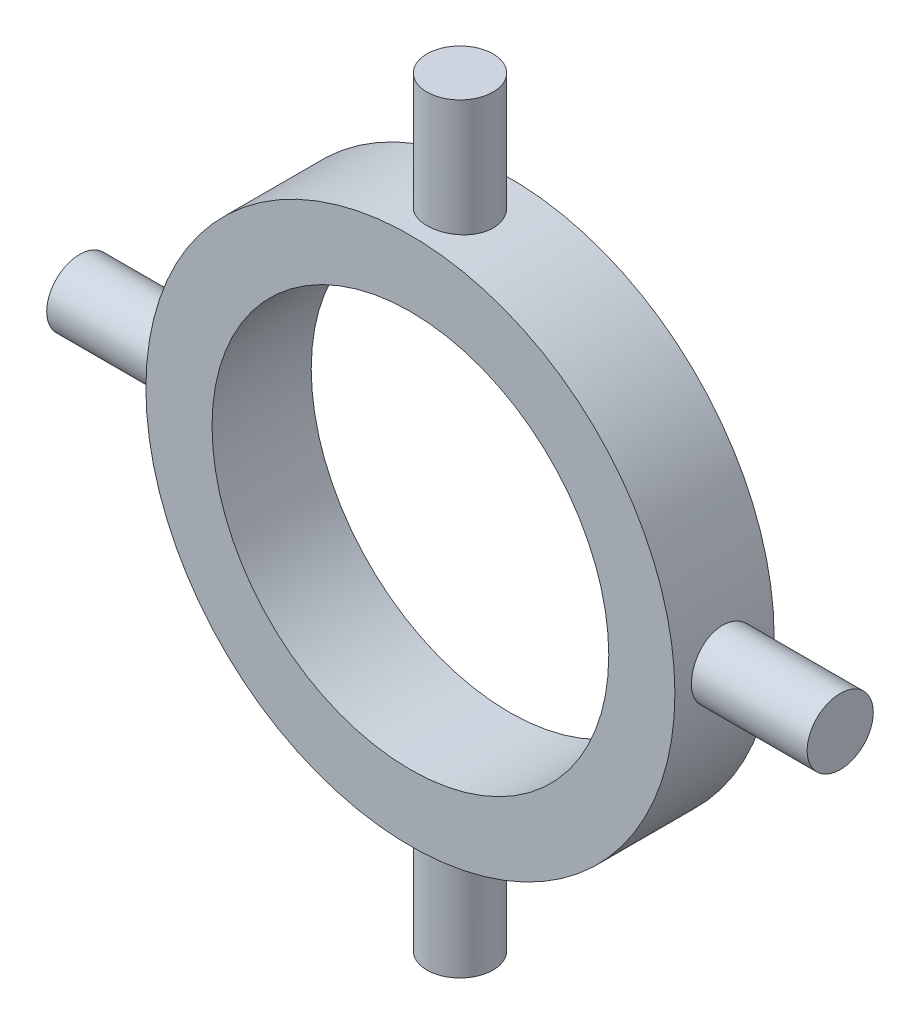
SolidWorks part; units mm, degrees
ref_plane "Alzado" through (0, 0, 0) normal (0, 0, 1) x (1, 0, 0)
ref_plane "Planta" through (0, 0, 0) normal (0, 1, 0) x (1, 0, 0)
ref_plane "Vista lateral" through (0, 0, 0) normal (1, 0, 0) x (0, 0, -1)
sketch "Croquis2" plane through (0, 0, 0) normal (0, 0, 1) x (1, 0, 0)
  circle A0 centre (0, 0) radius 40
  circle A1 centre (0, 0) radius 30
  dimension "D1" = 80
  dimension "D2" = 60
extrude "Saliente-Extruir1" add sketch "Croquis2" along normal mid plane 15
sketch "Croquis3" plane through (0, 0, 0) normal (0, 1, 0) x (1, 0, 0)
  circle A0 centre (0, 0) radius 5
  dimension "D1" = 10
extrude "Saliente-Extruir2" add sketch "Croquis3" along normal mid plane 115
sketch "Croquis4" plane through (0, 0, 0) normal (1, 0, 0) x (0, 0, -1)
  circle A0 centre (0, 0) radius 5
  dimension "D1" = 10
extrude "Saliente-Extruir3" add sketch "Croquis4" along normal mid plane 115
sketch "Croquis5" plane through (0, 0, 7.5) normal (0, 0, 1) x (1, 0, 0)
  circle A0 centre (0, 0) radius 30
extrude "Cortar-Extruir1" cut sketch "Croquis5" against normal blind 115
